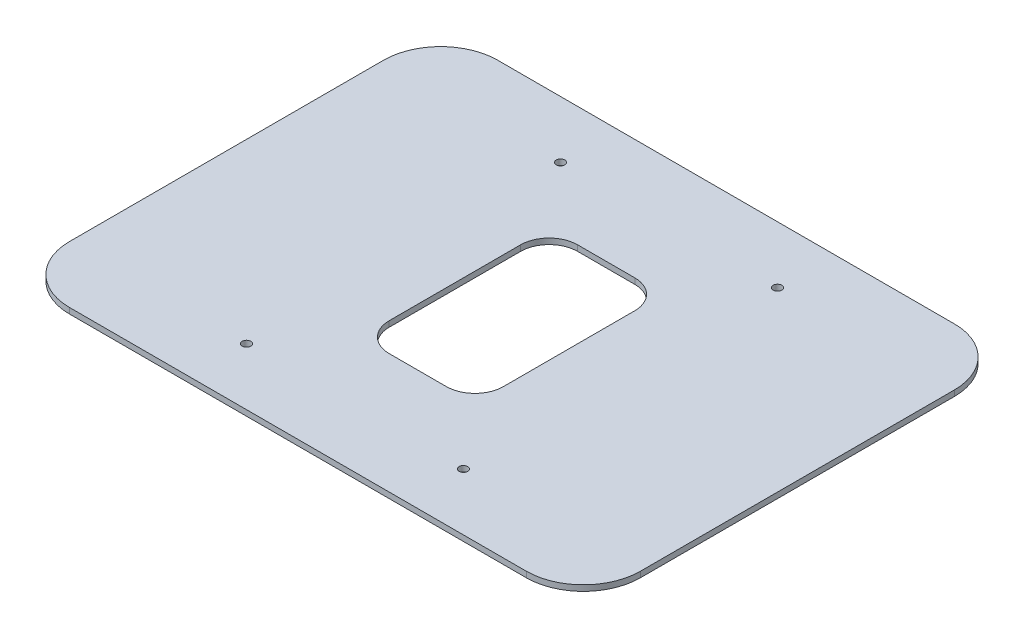
SolidWorks part; units mm, degrees
material "Cobre"
ref_plane "Plano frontal" through (0, 0, 0) normal (0, 0, 1) x (1, 0, 0)
ref_plane "Plano superior" through (0, 0, 0) normal (0, 1, 0) x (1, 0, 0)
ref_plane "Plano direito" through (0, 0, 0) normal (1, 0, 0) x (0, 0, -1)
sketch "Esboço1" plane through (0, 0, 0) normal (0, 1, 0) x (1, 0, 0)
  line L1 (-40.816, 183.1145) -> (119.184, 183.1145)
  line L2 (-60.816, 163.1145) -> (-60.816, 53.1145)
  line L3 (-40.816, 33.1145) -> (119.184, 33.1145)
  line L4 (139.184, 163.1145) -> (139.184, 53.1145)
  arc A0 (119.184, 183.1145) -> (139.184, 163.1145) centre (119.184, 163.1145) cw
  arc A1 (119.184, 33.1145) -> (139.184, 53.1145) centre (119.184, 53.1145) ccw
  arc A2 (-60.816, 53.1145) -> (-40.816, 33.1145) centre (-40.816, 53.1145) ccw
  arc A3 (-40.816, 183.1145) -> (-60.816, 163.1145) centre (-40.816, 163.1145) ccw
  dimension "D1" = 20
extrude "Ressalto-extrusão1" add sketch "Esboço1" along normal blind 2
sketch "Esboço2" plane through (0, 2, 0) normal (0, 1, 0) x (1, 0, 0)
  line L0 (91.4945, 56.1145) -> (86.184, 56.1145) construction
  line L1 (-0.816, 170.1145) -> (79.184, 170.1145) construction
  line L2 (86.9299, 160.1145) -> (86.184, 160.1145) construction
  line L3 (3.7486, 46.1145) -> (83.7486, 46.1145) construction
  line L4 (84.184, 158.1145) -> (84.184, 58.1145) construction
  line L5 (-8.562, 160.1145) -> (-7.816, 160.1145) construction
  line L6 (-3.9974, 56.1145) -> (-7.816, 56.1145) construction
  line L7 (-5.816, 158.1145) -> (-5.816, 58.1145) construction
  line L10 (-60.816, 163.1145) -> (-60.816, 53.1145) construction
  line L11 (139.184, 53.1145) -> (139.184, 163.1145) construction
  line L12 (119.184, 183.1145) -> (-40.816, 183.1145) construction
  line L14 (-40.816, 33.1145) -> (119.184, 33.1145) construction
  arc A0 (88.8664, 162.6145) -> (79.184, 170.1145) centre (79.184, 160.1145) ccw construction
  arc A1 (83.7486, 46.1145) -> (93.431, 53.6145) centre (83.7486, 56.1145) ccw construction
  arc A2 (-10.4985, 162.6145) -> (-0.816, 170.1145) centre (-0.816, 160.1145) cw construction
  arc A3 (-5.9339, 53.6145) -> (3.7486, 46.1145) centre (3.7486, 56.1145) ccw construction
  arc A4 (91.4945, 56.1145) -> (93.431, 53.6145) centre (91.4945, 54.1145) cw construction
  arc A5 (84.184, 58.1145) -> (86.184, 56.1145) centre (86.184, 58.1145) ccw construction
  arc A6 (86.9299, 160.1145) -> (88.8664, 162.6145) centre (86.9299, 162.1145) ccw construction
  arc A7 (84.184, 158.1145) -> (86.184, 160.1145) centre (86.184, 158.1145) cw construction
  arc A8 (-7.816, 160.1145) -> (-5.816, 158.1145) centre (-7.816, 158.1145) cw construction
  arc A9 (-8.562, 160.1145) -> (-10.4985, 162.6145) centre (-8.562, 162.1145) cw construction
  arc A10 (-7.816, 56.1145) -> (-5.816, 58.1145) centre (-7.816, 58.1145) ccw construction
  arc A11 (-3.9974, 56.1145) -> (-5.9339, 53.6145) centre (-3.9974, 54.1145) ccw construction
  circle A12 centre (1.184, 163.1145) radius 1.5
  circle A13 centre (77.184, 163.1145) radius 1.5
  circle A14 centre (77.184, 53.1145) radius 1.5
  circle A15 centre (1.184, 53.1145) radius 1.5
  dimension "D1" = 10
  dimension "D2" = 2
  dimension "D9" = 7
  dimension "D10" = 7
  dimension "D11" = 3
  dimension "D12" = 7
  dimension "D13" = 7
  dimension "D14" = 3
  dimension "D15" = 7
  dimension "D16" = 7
  dimension "D17" = 3
  dimension "D3" = 100
  dimension "D4" = 55
  dimension "D5" = 100
  dimension "D6" = 55
  dimension "D7" = 13
  dimension "D8" = 13
extrude "Corte-extrusão1" cut sketch "Esboço2" against normal blind 10
sketch "Esboço3" plane through (0, 2, 0) normal (0, 1, 0) x (1, 0, 0)
  line L0 (119.184, 183.1145) -> (-40.816, 183.1145) construction
  line L1 (29.184, 141.1145) -> (49.184, 141.1145)
  line L2 (19.184, 131.1145) -> (19.184, 85.1145)
  line L3 (29.184, 75.1145) -> (49.184, 75.1145)
  line L4 (59.184, 131.1145) -> (59.184, 85.1145)
  line L5 (-40.816, 33.1145) -> (119.184, 33.1145) construction
  line L6 (-60.816, 163.1145) -> (-60.816, 53.1145) construction
  line L7 (139.184, 53.1145) -> (139.184, 163.1145) construction
  arc A0 (49.184, 141.1145) -> (59.184, 131.1145) centre (49.184, 131.1145) cw
  arc A1 (49.184, 75.1145) -> (59.184, 85.1145) centre (49.184, 85.1145) ccw
  arc A2 (19.184, 85.1145) -> (29.184, 75.1145) centre (29.184, 85.1145) ccw
  arc A3 (29.184, 141.1145) -> (19.184, 131.1145) centre (29.184, 131.1145) ccw
  dimension "D5" = 10
  dimension "D1" = 42
  dimension "D2" = 42
  dimension "D3" = 80
  dimension "D4" = 80
extrude "Corte-extrusão2" cut sketch "Esboço3" against normal blind 10
